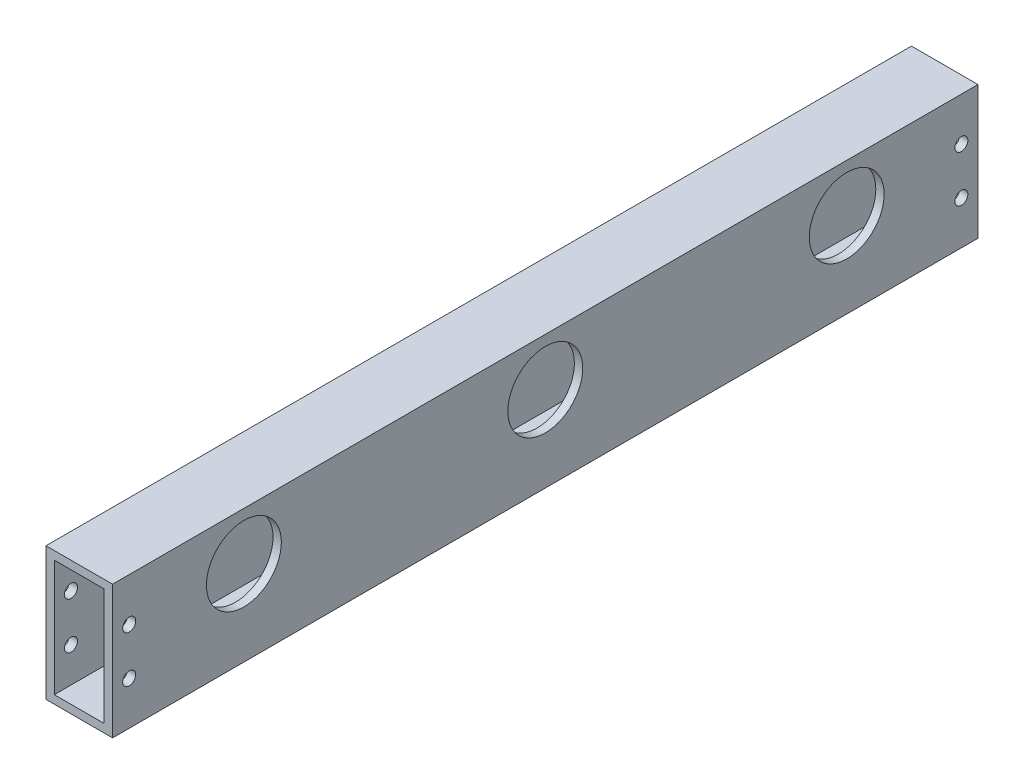
SolidWorks part; units mm, degrees
material "6061-T6 (SS)"
ref_plane "Front Plane" through (0, 0, 0) normal (0, 0, 1) x (1, 0, 0)
ref_plane "Top Plane" through (0, 0, 0) normal (0, 1, 0) x (1, 0, 0)
ref_plane "Right Plane" through (0, 0, 0) normal (1, 0, 0) x (0, 0, -1)
sketch "Sketch1" plane through (0, 0, 0) normal (1, 0, 0) x (0, 0, -1)
  line L0 (-115, 7.112) -> (0, 7.112) construction
  line L1 (165.1, 25.4) -> (-165.1, 25.4)
  line L2 (165.1, 25.4) -> (165.1, -25.4)
  line L3 (165.1, -25.4) -> (-165.1, -25.4)
  line L4 (-165.1, 25.4) -> (-165.1, -25.4)
  line L5 (165.1, 25.4) -> (-165.1, -25.4) construction
  line L6 (165.1, -25.4) -> (-165.1, 25.4) construction
  line L7 (115, 7.112) -> (0, 7.112) construction
  line L8 (-115, 7.112) -> (0, 7.112) construction
  line L9 (-115, 23.112) -> (0, 23.112) construction
  line L10 (-115, -8.888) -> (0, -8.888) construction
  circle A1 centre (0, 7.112) radius 14.2875
  circle A2 centre (-115, 7.112) radius 14.2875
  circle A3 centre (115, 7.112) radius 14.2875
  circle A4 centre (-115, 7.112) radius 41.275 construction
  circle A5 centre (0, 7.112) radius 41.275 construction
  circle A6 centre (115, 7.112) radius 41.275 construction
  arc A7 (-115, 23.112) -> (-115, -8.888) centre (-115, 7.112) ccw construction
  arc A8 (0, -8.888) -> (0, 23.112) centre (0, 7.112) ccw construction
  point P0 (0, 0)
  point P15 (-57.5, 7.112)
  point P17 (-156.275, 7.112)
  dimension "D3" = 28.575
  dimension "D6" = 82.55
  dimension "D7" = 8.825
  dimension "D8" = 16
  dimension "D1" = 50.8
  dimension "D2" = 330.2
  dimension "D4" = 32.512
  dimension "D5" = 115
extrude "Boss-Extrude1" add sketch "Sketch1" along normal blind 25.4 contours L1 L4 L3 L2 A3 A2 A1
shell "Shell1" thickness 3.175
sketch "Sketch2" plane through (25.4, 0, 0) normal (1, 0, 0) x (0, 0, -1)
  line L0 (-158.75, -8.89) -> (-158.75, 8.89) construction
  line L1 (-165.1, 25.4) -> (-165.1, -25.4) construction
  point P2 (-158.75, 0)
  point P3 (-165.1, 0)
  dimension "D1" = 17.78
  dimension "D2" = 6.35
hole_wizard "#9 (0.196) Diameter Hole1" positions "Sketch3" profile "Sketch5" hole size "#9" standard "ANSI Inch" end condition through all
sketch "Sketch3" plane through (25.4, 0, 0) normal (1, 0, 0) x (0, 0, -1)
  point P0 (-158.75, 8.89)
  point P3 (-158.75, -8.89)
sketch "Sketch5" plane through (25.4, 8.89, 158.75) normal (0, 1, 0) x (0, 0, -1)
  line L0 (0, 0) -> (0, 25.4)
  line L1 (0, 25.4) -> (2.4892, 25.4)
  line L2 (2.4892, 25.4) -> (2.4892, 0)
  line L5 (2.4892, 0) -> (0, 0)
  line L11 (0, -6.35) -> (0, 107.95) construction
  dimension "Thru Hole Dia." = 4.9784
  dimension "Thru Hole Depth" = 25.4
mirror "Mirror1" about plane through (0, 0, 0) normal (0, 0, 1) of "#9 (0.196) Diameter Hole1"
